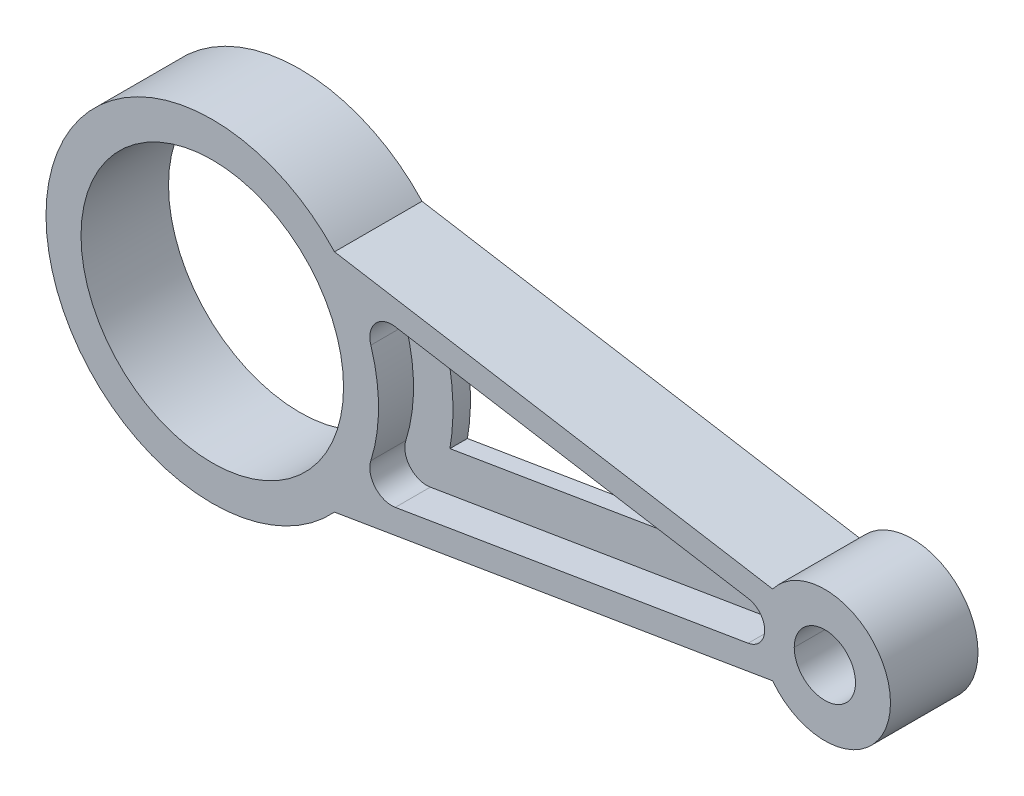
SolidWorks part; units mm, degrees
material "Plain Carbon Steel"
ref_plane "Front Plane" through (0, 0, 0) normal (0, 0, 1) x (1, 0, 0)
ref_plane "Top Plane" through (0, 0, 0) normal (0, 1, 0) x (1, 0, 0)
ref_plane "Right Plane" through (0, 0, 0) normal (1, 0, 0) x (0, 0, -1)
sketch "Sketch1" plane through (0, 0, 0) normal (0, 0, 1) x (1, 0, 0)
  line L0 (-102.3917, 0) -> (200.7225, 0) construction
  line L1 (27.9355, 25.7606) -> (128.0638, 9.0844)
  line L2 (27.9355, -25.7606) -> (128.0638, -9.0844)
  circle A0 centre (0, 0) radius 30
  arc A1 (27.9355, 25.7606) -> (27.9355, -25.7606) centre (0, 0) ccw
  circle A2 centre (140, 0) radius 7
  arc A3 (128.0638, -9.0844) -> (128.0638, 9.0844) centre (140, 0) ccw
  dimension "D2" = 60
  dimension "D3" = 76
  dimension "D4" = 30
  dimension "D5" = 14
  dimension "D1" = 140
extrude "Boss-Extrude1" add sketch "Sketch1" along normal mid plane 20
sketch "Sketch2" plane through (0, 0, 10) normal (0, 0, 1) x (1, 0, 0)
  line L0 (0, 0) -> (213.9156, 0) construction
  line L1 (41.8286, 17.871) -> (122.4784, 4.4389)
  line L2 (122.4784, -4.4389) -> (41.8286, -17.871)
  line L3 (128.0638, 9.0844) -> (27.9355, 25.7606) construction
  arc A0 (36.2389, -11.4344) -> (36.2389, 11.4344) centre (0, 0) ccw
  circle A1 centre (0, 0) radius 30 construction
  arc A3 (36.2389, -11.4344) -> (41.8286, -17.871) centre (41.0071, -12.9389) ccw
  arc A4 (36.2389, 11.4344) -> (41.8286, 17.871) centre (41.0071, 12.9389) cw
  arc A5 (122.4784, 4.4389) -> (122.4784, -4.4389) centre (121.7391, 0) cw
  dimension "D1" = 8
  dimension "D3" = 4.5
  dimension "D4" = 5
  dimension "D2" = 5.5
extrude "Cut-Extrude1" cut sketch "Sketch2" against normal blind 8
mirror "Mirror1" about plane through (0, 0, 0) normal (0, 0, 1) of "Cut-Extrude1"
split line "Split Line1"
sketch "Sketch3" plane through (0, 0, 2) normal (0, 0, 1) x (1, 0, 0)
  line L0 (41.8286, -17.871) -> (122.4784, -4.4389) construction
  line L1 (122.4784, 4.4389) -> (41.8286, 17.871) construction
  line L2 (41.8286, -17.871) -> (122.4784, -4.4389)
  line L3 (122.4784, 4.4389) -> (41.8286, 17.871)
  line L4 (94.3478, 0) -> (46.3142, 7.9999)
  line L5 (46.3142, -7.9999) -> (94.3478, 0)
  arc A0 (122.4784, -4.4389) -> (122.4784, 4.4389) centre (121.7391, 0) ccw construction
  arc A1 (36.2389, -11.4344) -> (41.8286, -17.871) centre (41.0071, -12.9389) ccw construction
  arc A2 (36.2389, -11.4344) -> (36.2389, 11.4344) centre (0, 0) ccw construction
  arc A3 (41.8286, 17.871) -> (36.2389, 11.4344) centre (41.0071, 12.9389) ccw construction
  arc A4 (122.4784, -4.4389) -> (122.4784, 4.4389) centre (121.7391, 0) ccw
  arc A5 (36.2389, -11.4344) -> (41.8286, -17.871) centre (41.0071, -12.9389) ccw
  arc A6 (36.2389, -11.4344) -> (36.2389, 11.4344) centre (0, 0) ccw
  arc A7 (41.8286, 17.871) -> (36.2389, 11.4344) centre (41.0071, 12.9389) ccw
  arc A8 (46.3142, 7.9999) -> (46.3142, 7.9999) centre (46.3142, 7.9999) ccw
  arc A9 (46.3142, -7.9999) -> (46.3142, 7.9999) centre (0, 0) ccw
  arc A10 (46.3142, -7.9999) -> (46.3142, -7.9999) centre (46.3142, -7.9999) ccw
  arc A11 (94.3478, 0) -> (94.3478, 0) centre (94.3478, 0) ccw
  dimension "D1" = 9
extrude "Cut-Extrude2" cut sketch "Sketch3" against normal through all contours A9 L5 L4
